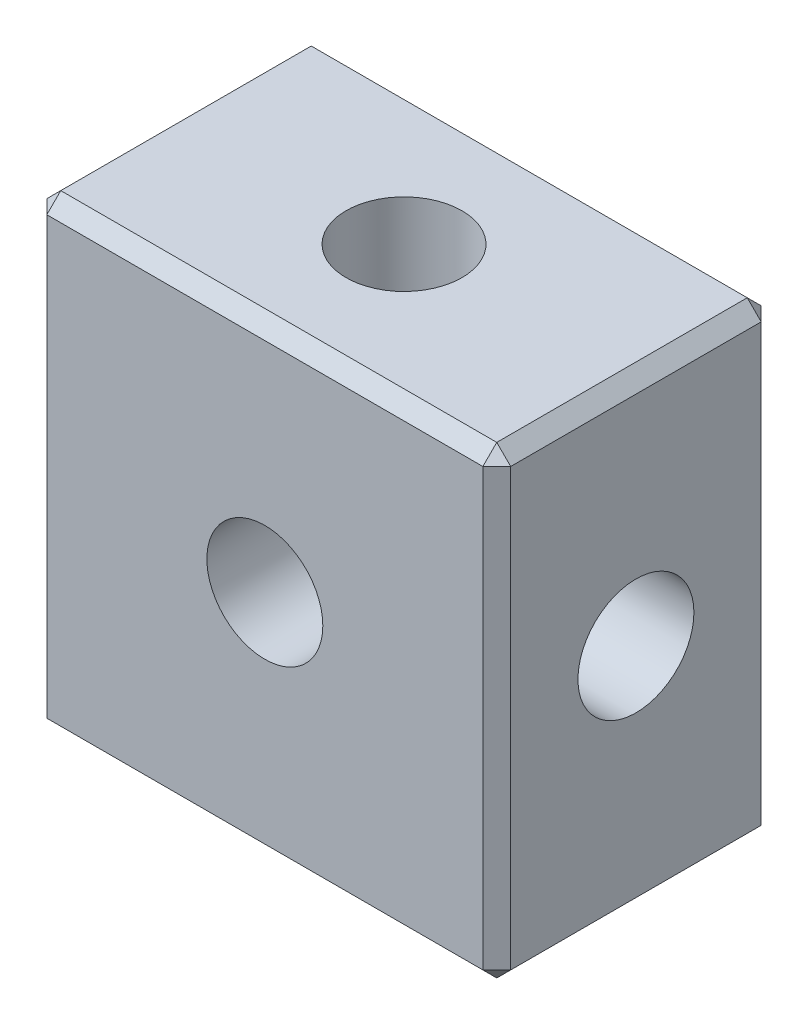
SolidWorks part; units mm, degrees
material "6061 合金"
ref_plane "前视基准面" through (0, 0, 0) normal (0, 0, 1) x (1, 0, 0)
ref_plane "上视基准面" through (0, 0, 0) normal (0, 1, 0) x (1, 0, 0)
ref_plane "右视基准面" through (0, 0, 0) normal (1, 0, 0) x (0, 0, -1)
sketch "草图1" plane through (0, 0, 0) normal (0, 0, 1) x (1, 0, 0)
  line L1 (-5, -5) -> (5, -5)
  line L2 (-5, -5) -> (-5, 5)
  line L3 (-5, 5) -> (5, 5)
  line L4 (5, -5) -> (5, 5)
  line L5 (0, 5) -> (0, -5) construction
  line L6 (-5, 0) -> (5, 0) construction
  point P0 (0, 0)
  dimension "D1" = 10
extrude "凸台-拉伸1" add sketch "草图1" along normal mid plane 6
hole_wizard "螺纹孔1" positions "草图2" profile "草图3" tap size "M3" standard "GB" end condition through all
sketch "草图2" plane through (0, 0, 3) normal (0, 0, 1) x (1, 0, 0)
  point P0 (0, 0)
cosmetic thread "孔螺蚊线1"
sketch "草图3" plane through (0, 0, 3) normal (1, 0, 0) x (0, -1, 0)
  line L0 (0, 0) -> (0, 6)
  line L1 (0, 6) -> (1.25, 6)
  line L2 (1.25, 6) -> (1.25, 0)
  line L5 (1.25, 0) -> (0, 0)
  line L11 (0, -6.35) -> (0, 107.95) construction
  dimension "通孔螺纹孔钻头直径" = 2.5
  dimension "通孔螺纹孔钻头深度" = 6
hole_wizard " 螺纹孔2" positions "草图4" profile "草图5" tap size "M3" standard "GB" end condition through all
sketch "草图4" plane through (5, 0, 0) normal (1, 0, 0) x (0, 0, -1)
  point P0 (0, 0)
sketch "草图5" plane through (5, 0, 0) normal (0, 1, 0) x (0, 0, -1)
  line L0 (0, 0) -> (0, 10)
  line L1 (0, 10) -> (1.25, 10)
  line L2 (1.25, 10) -> (1.25, 0)
  line L5 (1.25, 0) -> (0, 0)
  line L11 (0, -6.35) -> (0, 107.95) construction
  dimension "通孔螺纹孔钻头直径" = 2.5
  dimension "通孔螺纹孔钻头深度" = 10
cosmetic thread "孔螺蚊线2"
hole_wizard "螺纹孔3" positions "草图6" profile "草图7" tap size "M3" standard "GB" end condition through all
sketch "草图6" plane through (0, -5, 0) normal (0, -1, 0) x (-1, 0, 0)
  point P0 (0, 0)
sketch "草图7" plane through (0, -5, 0) normal (1, 0, 0) x (0, 0, -1)
  line L0 (0, 0) -> (0, 10)
  line L1 (0, 10) -> (1.25, 10)
  line L2 (1.25, 10) -> (1.25, 0)
  line L5 (1.25, 0) -> (0, 0)
  line L11 (0, -6.35) -> (0, 107.95) construction
  dimension "通孔螺纹孔钻头直径" = 2.5
  dimension "通孔螺纹孔钻头深度" = 10
cosmetic thread "孔螺蚊线3" parameters "D2"=3
chamfer "倒角1" distance 0.3 angle 45 12 edges at (-5, -5, 0) (-5, 0, -3) (0, -5, -3) (5, -5, 0) (5, 0, -3) (5, 0, 3) (0, -5, 3) (-5, 0, 3) (0, 5, 3) (-5, 5, 0) (0, 5, -3) (5, 5, 0)
